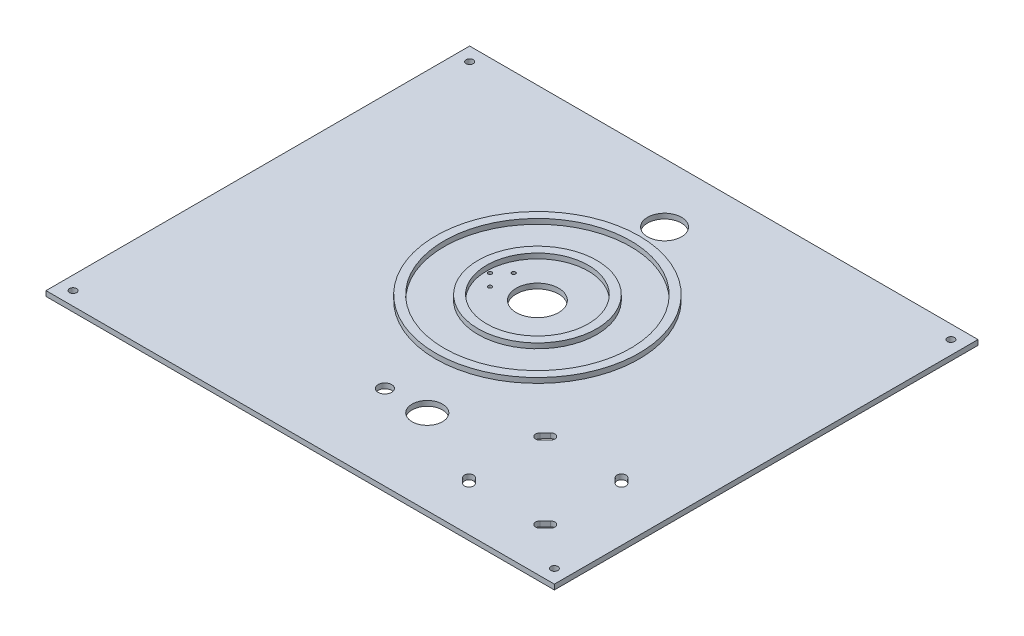
SolidWorks part; units mm, degrees
ref_plane "Front Plane" through (0, 0, 0) normal (0, 0, 1) x (1, 0, 0)
ref_plane "Top Plane" through (0, 0, 0) normal (0, 1, 0) x (1, 0, 0)
ref_plane "Right Plane" through (0, 0, 0) normal (1, 0, 0) x (0, 0, -1)
sketch "Sketch1" plane through (0, 0, 0) normal (0, 1, 0) x (1, 0, 0)
  line L1 (-150, 110) -> (150, 110)
  line L2 (-150, 110) -> (-150, -110)
  line L3 (-150, -110) -> (150, -110)
  line L4 (150, 110) -> (150, -110)
  line L5 (-150, 110) -> (150, -110) construction
  line L6 (-150, -110) -> (150, 110) construction
  point P0 (0, 0)
  dimension "D1" = 220
  dimension "D2" = 300
extrude "Boss-Extrude1" add sketch "Sketch1" along normal blind 3
sketch "Sketch2" plane through (0, 3, 0) normal (0, 1, 0) x (1, 0, 0)
  circle A0 centre (0, 0) radius 12.5
  dimension "D1" = 25
extrude "Cut-Extrude1" cut sketch "Sketch2" against normal blind 3
sketch "Sketch3" plane through (0, 3, 0) normal (0, 1, 0) x (1, 0, 0)
  circle A0 centre (0, 0) radius 30
  circle A1 centre (0, 0) radius 35
  circle A2 centre (0, 0) radius 55
  circle A3 centre (0, 0) radius 60
  dimension "D1" = 60
  dimension "D2" = 70
  dimension "D3" = 110
  dimension "D4" = 120
extrude "Boss-Extrude2" add sketch "Sketch3" along normal blind 3 contours A3 A2 | A1 A0
sketch "Sketch4" plane through (0, 0, 0) normal (0, -1, 0) x (1, 0, 0)
  circle A0 centre (-20.9915, 7) radius 1.1
  circle A1 centre (-27.9915, 0) radius 1.1
  circle A2 centre (-20.9915, -7) radius 1.1
  dimension "D1" = 2.2
extrude "Cut-Extrude2" cut sketch "Sketch4" against normal up to next
sketch "Sketch5" plane through (0, 3, 0) normal (0, 1, 0) x (1, 0, 0)
  circle A0 centre (0, 75) radius 10
  dimension "D2" = 20
  dimension "D1" = 75
extrude "Cut-Extrude3" cut sketch "Sketch5" against normal up to next
sketch "Sketch6" plane through (0, 3, 0) normal (0, 1, 0) x (1, 0, 0)
  line L1 (-150, -110) -> (150, -110)
  line L2 (-150, -110) -> (-150, -140)
  line L3 (-150, -140) -> (150, -140)
  line L4 (150, -110) -> (150, -140)
  dimension "D1" = 30
extrude "Boss-Extrude3" add sketch "Sketch6" against normal up to surface (3 mm away) up to face at (0, 0, -65)
sketch "Sketch7" plane through (0, 3, 0) normal (0, 1, 0) x (1, 0, 0)
  line L0 (-150, 110) -> (-150, -140) construction
  line L1 (150, 110) -> (-150, 110) construction
  line L2 (150, -140) -> (150, 110) construction
  line L3 (-150, -140) -> (150, -140) construction
  circle A0 centre (-142, 102) radius 2.1
  circle A1 centre (142, 102) radius 2.1
  circle A2 centre (142, -132) radius 2.1
  circle A3 centre (-142, -132) radius 2.1
  dimension "D1" = 4.2
  dimension "D2" = 8
  dimension "D3" = 8
  dimension "D4" = 8
  dimension "D5" = 8
extrude "Cut-Extrude4" cut sketch "Sketch7" against normal up to next
sketch "Sketch9" plane through (0, 3, 0) normal (0, 1, 0) x (1, 0, 0)
  line L16 (73.35, -65.692) -> (70.3693, -68.7996) construction
  line L17 (75.2521, -67.5165) -> (72.2714, -70.6241)
  line L18 (71.4479, -63.8675) -> (68.4671, -66.9751)
  line L19 (70.3693, -110.7554) -> (73.35, -113.7362) construction
  line L20 (72.233, -108.8917) -> (75.2137, -111.8725)
  line L21 (68.5056, -112.6191) -> (71.4863, -115.5999)
  line L22 (118.3821, -110.7234) -> (115.3372, -113.7682) construction
  line L23 (120.2458, -112.5871) -> (117.2009, -115.6319)
  line L24 (116.5184, -108.8597) -> (113.4735, -111.9045)
  line L25 (115.3372, -65.7234) -> (118.3821, -68.7682) construction
  line L26 (117.2009, -63.8597) -> (120.2458, -66.9045)
  line L27 (113.4735, -67.5871) -> (116.5184, -70.6319)
  arc A3 (75.2521, -67.5165) -> (71.4479, -63.8675) centre (73.35, -65.692) ccw
  arc A4 (68.4671, -66.9751) -> (72.2714, -70.6241) centre (70.3693, -68.7996) ccw
  arc A5 (72.233, -108.8917) -> (68.5056, -112.6191) centre (70.3693, -110.7554) ccw
  arc A6 (71.4863, -115.5999) -> (75.2137, -111.8725) centre (73.35, -113.7362) ccw
  arc A7 (120.2458, -112.5871) -> (116.5184, -108.8597) centre (118.3821, -110.7234) ccw
  arc A8 (113.4735, -111.9045) -> (117.2009, -115.6319) centre (115.3372, -113.7682) ccw
  arc A9 (117.2009, -63.8597) -> (113.4735, -67.5871) centre (115.3372, -65.7234) ccw
  arc A10 (116.5184, -70.6319) -> (120.2458, -66.9045) centre (118.3821, -68.7682) ccw
  point P0 (0, 0)
  point P9 (71.8596, -112.2458)
  point P15 (116.8596, -112.2458)
  point P18 (71.8596, -67.2458)
  point P27 (116.8596, -67.2458)
  point P34 (0, 0)
  point P35 (0, 0)
  point P36 (0, 0)
  point P37 (0, 0)
  point P38 (71.9119, -66.932)
  point P39 (70.6605, -68.6793)
  point P40 (73.489, -65.3653)
  point P41 (70.2721, -68.7672)
  point P42 (73.6416, -65.2033)
  point P43 (71.8596, -67.2444)
  point P44 (70.3693, -68.7996)
  point P45 (118.3544, -69.1585)
  point P46 (115.0668, -114.4998)
  point P47 (70.3693, -111.4264)
  dimension "D1" = 45
  dimension "D2" = 45
extrude "Cut-Extrude5" cut sketch "Sketch9" against normal up to next
sketch "Sketch10" plane through (0, 3, 0) normal (0, 1, 0) x (1, 0, 0)
  line L0 (-150, -140) -> (150, -140) construction
  circle A0 centre (0, -90) radius 4
  circle A1 centre (25, -90) radius 9
  dimension "D1" = 50
  dimension "D2" = 18
  dimension "D3" = 8
  dimension "D4" = 25
extrude "Cut-Extrude6" cut sketch "Sketch10" against normal up to next
